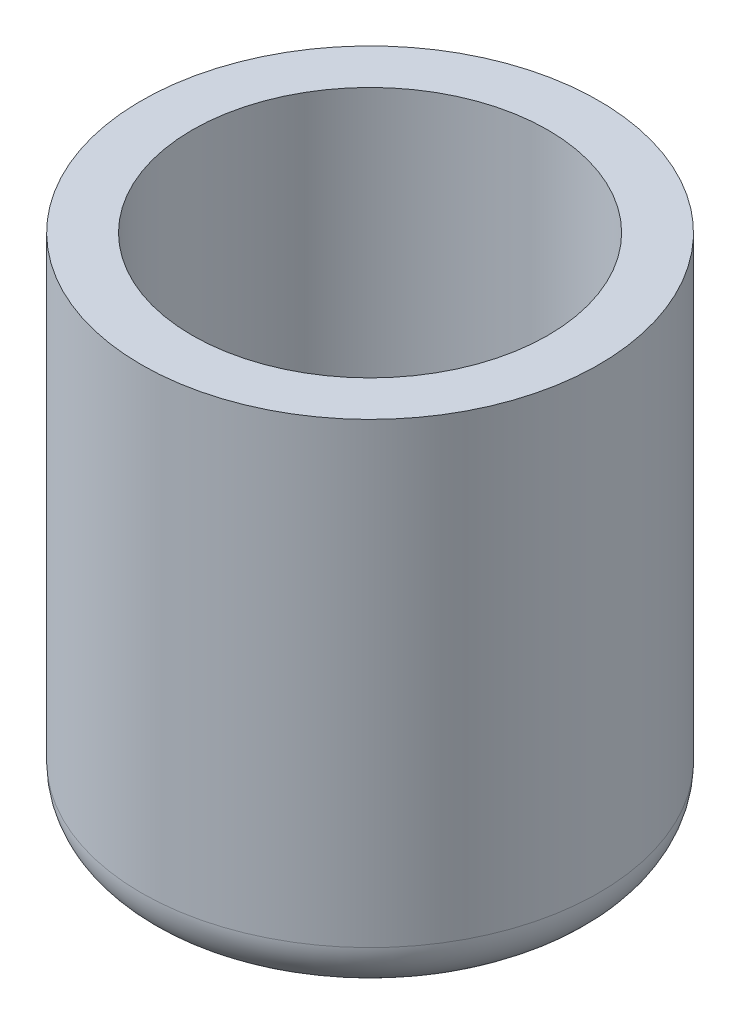
SolidWorks part; units mm, degrees
ref_plane "Front Plane" through (0, 0, 0) normal (0, 0, 1) x (1, 0, 0)
ref_plane "Top Plane" through (0, 0, 0) normal (0, 1, 0) x (1, 0, 0)
ref_plane "Right Plane" through (0, 0, 0) normal (1, 0, 0) x (0, 0, -1)
sketch "Sketch1" plane through (0, 0, 0) normal (0, 1, 0) x (1, 0, 0)
  circle A0 centre (0, 0) radius 4.5
  dimension "D1" = 9
extrude "Boss-Extrude1" add sketch "Sketch1" along normal blind 10
shell "Shell1" thickness 1
sketch "Sketch4" plane through (0, 0, 0) normal (0, 0, 1) x (1, 0, 0)
  line L0 (3.5, 1) -> (-3.5, 1) construction
  line L3 (0, 3.5) -> (0, -1.5)
  arc A0 (0, 3.5) -> (0, -1.5) centre (0, 1) cw
  point P0 (0, 1)
  point P6 (0, 0)
  point P8 (0, 1)
  dimension "D1" = 2.5
revolve "Cut-Revolve1" cut sketch "Sketch4" angle 360 about L3
fillet "Fillet1" radius 1 1 edges at (0, 0, 4.5)
